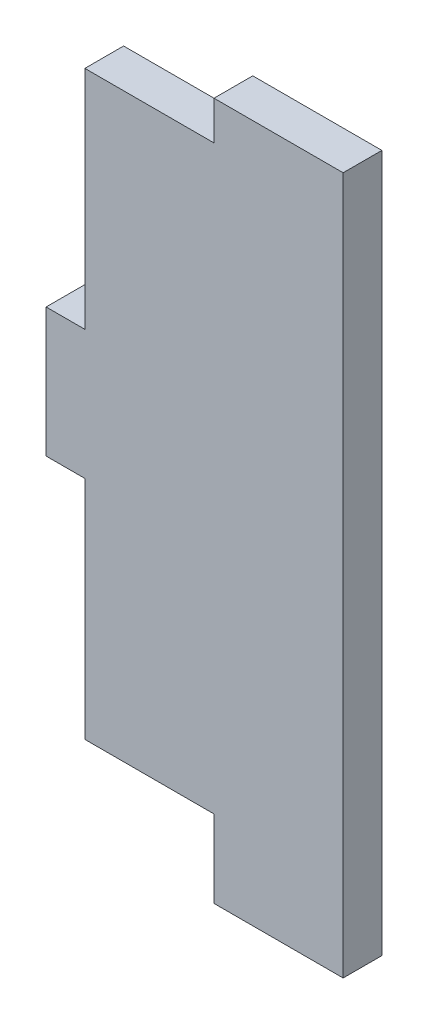
SolidWorks part; units mm, degrees
ref_plane "Front Plane" through (0, 0, 0) normal (0, 0, 1) x (1, 0, 0)
ref_plane "Top Plane" through (0, 0, 0) normal (0, 1, 0) x (1, 0, 0)
ref_plane "Right Plane" through (0, 0, 0) normal (1, 0, 0) x (0, 0, -1)
sketch "Sketch1" plane through (0, 0, 0) normal (0, 0, 1) x (1, 0, 0)
  line L0 (0, 0) -> (10, 0)
  line L1 (10, 0) -> (10, -6)
  line L2 (10, -6) -> (20, -6)
  line L3 (20, -6) -> (20, 48)
  line L4 (20, 48) -> (10, 48)
  line L5 (10, 48) -> (10, 45)
  line L6 (10, 45) -> (0, 45)
  line L7 (0, 45) -> (0, 27.5)
  line L8 (0, 17.5) -> (0, 0)
  line L9 (0, 27.5) -> (-3, 27.5)
  line L11 (0, 17.5) -> (-3, 17.5)
  line L12 (-3, 27.5) -> (-3, 17.5)
  dimension "D1" = 45
  dimension "D2" = 10
  dimension "D3" = 10
  dimension "D4" = 3
  dimension "D5" = 10
  dimension "D6" = 6
extrude "Boss-Extrude1" add sketch "Sketch1" along normal blind 3
